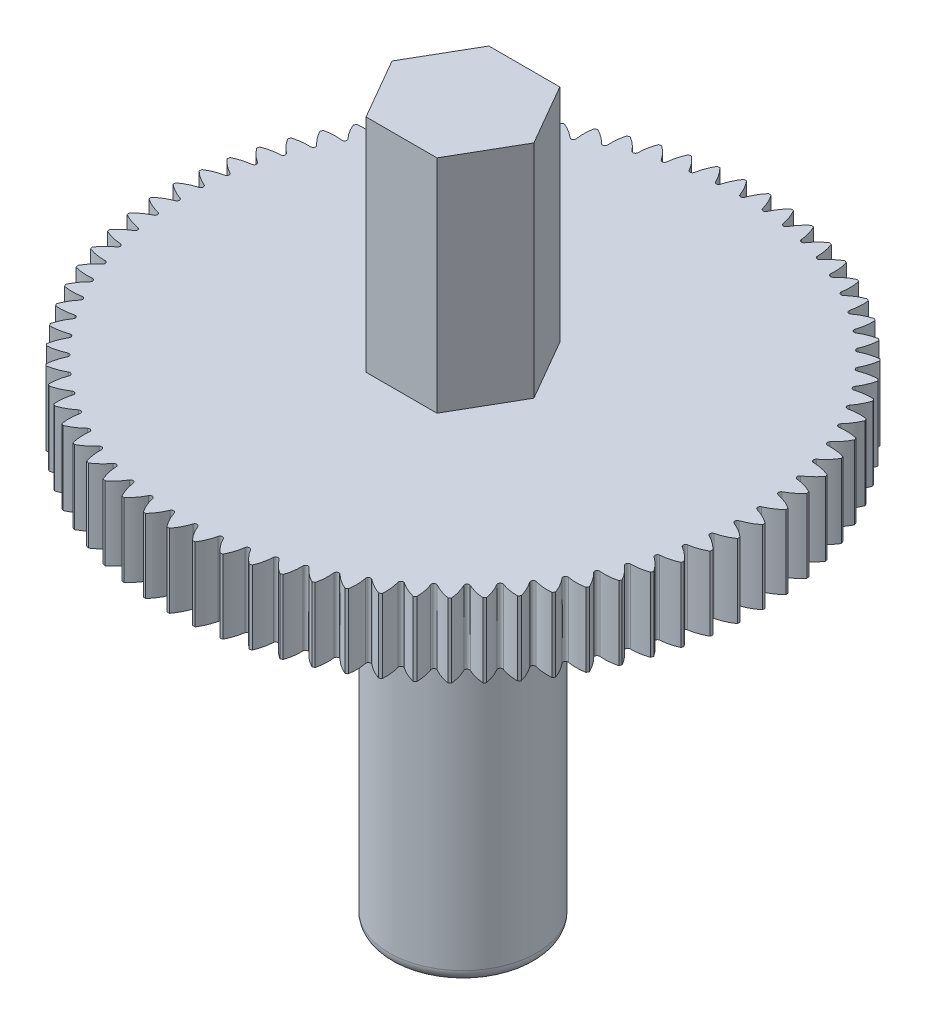
SolidWorks part; units mm, degrees
ref_plane "Ön Düzlem" through (0, 0, 0) normal (0, 0, 1) x (1, 0, 0)
ref_plane "Üst Düzlem" through (0, 0, 0) normal (0, 1, 0) x (1, 0, 0)
ref_plane "Sağ Düzlem" through (0, 0, 0) normal (1, 0, 0) x (0, 0, -1)
sketch "Çizim2" plane through (0, 0, 0) normal (0, 0, 1) x (1, 0, 0)
  line L0 (0, 0) -> (3, 0)
  line L1 (3, 0) -> (3, 17)
  line L2 (3, 17) -> (12, 17)
  line L3 (12, 17) -> (12, 20)
  line L4 (12, 20) -> (3, 20)
  line L5 (3, 20) -> (3, 29)
  line L6 (3, 29) -> (0, 29)
  line L7 (0, 29) -> (0, 0)
  dimension "D1" = 17
  dimension "D2" = 9
  dimension "D3" = 3
  dimension "D4" = 3
  dimension "D5" = 29
revolve "Döndür1" add sketch "Çizim2" angle 360 about L7
fillet "Radyus1" radius 0.5 1 edges at (-3, 0, 0)
sketch "Çizim3" plane through (0, 29, 0) normal (0, 1, 0) x (1, 0, 0)
  line L1 (1.4434, -2.5) -> (2.8868, 0)
  line L2 (2.8868, 0) -> (1.4434, 2.5)
  line L3 (1.4434, 2.5) -> (-1.4434, 2.5)
  line L4 (-1.4434, 2.5) -> (-2.8868, 0)
  line L5 (-2.8868, 0) -> (-1.4434, -2.5)
  line L6 (-1.4434, -2.5) -> (1.4434, -2.5)
  circle A0 centre (0, 0) radius 2.5 construction
  dimension "D1" = 5
extrude "Kes-Ekstrüzyon1" cut sketch "Çizim3" against normal blind 9 flip side to cut
sketch "Çizim4" plane through (0, 20, 0) normal (0, 1, 0) x (1, 0, 0)
  line L0 (0, 0) -> (0, 15.8316) construction
  circle A0 centre (0, 0) radius 12 construction
  circle A1 centre (0, 0) radius 12
  arc A2 (-0.45, 11.9916) -> (-0.0937, 11.3725) centre (-1.9774, 10.7005) cw
  arc A3 (0.0946, 11.3724) -> (0.45, 11.9916) centre (2, 10.6902) cw
  arc A4 (-0.0937, 11.3725) -> (0.0946, 11.3724) centre (0.0004, 11.4061) ccw
  point P13 (0, 11)
  circle M3 centre (0, 0) radius 12
  dimension "D3" = 2
  dimension "D5" = 0.1
  dimension "D1" = 0.9
  dimension "D2" = 2
  dimension "D4" = 11
extrude "Kes-Ekstrüzyon2" cut sketch "Çizim4" against normal blind 4 contours L0 A4 A3 A1 | A4 L0 A2 M3
sketch "Çizim5" plane through (0, 0, 0) normal (0, 0, 1) x (1, 0, 0)
  line L0 (0, 29) -> (0, -1.9003) construction
  line L1 (-1.4434, 29) -> (1.4434, 29) construction
pattern_circular "Dairesel Kaplama1" count 75 over 360 about axis through (0, 0, 0) along (0, 1, 0) of "Kes-Ekstrüzyon2"
